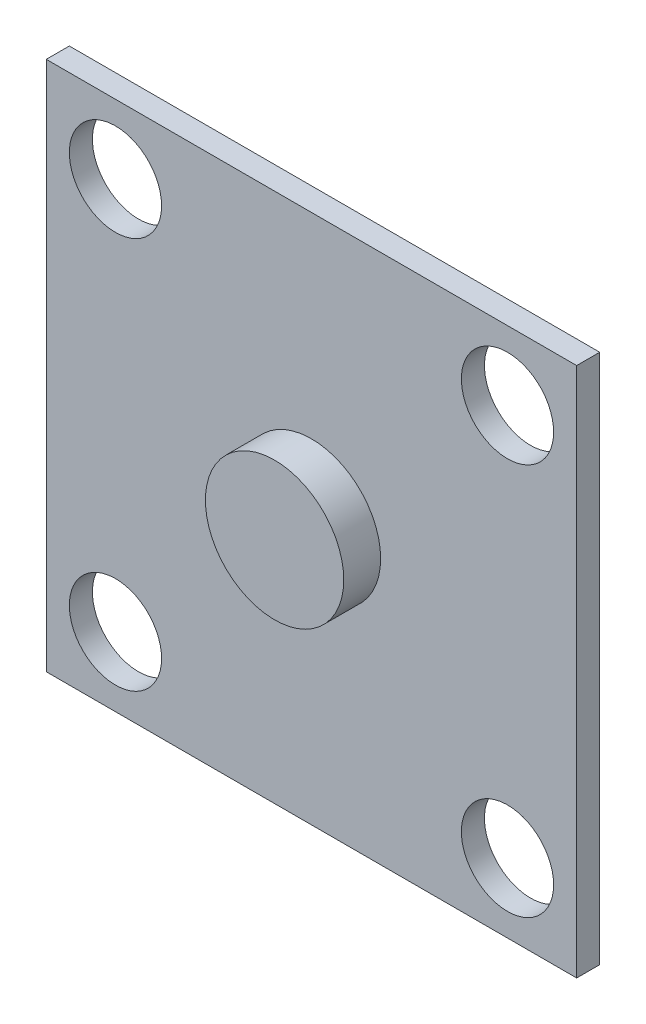
SolidWorks part; units mm, degrees
ref_plane "前视基准面" through (0, 0, 0) normal (0, 0, 1) x (1, 0, 0)
ref_plane "上视基准面" through (0, 0, 0) normal (0, 1, 0) x (1, 0, 0)
ref_plane "右视基准面" through (0, 0, 0) normal (1, 0, 0) x (0, 0, -1)
sketch "草图1" plane through (0, 0, 0) normal (0, 0, 1) x (1, 0, 0)
  line L1 (-11.776, 14.1224) -> (5.224, 14.1224) construction
  line L2 (-11.776, 14.1224) -> (-11.776, -2.8776) construction
  line L3 (-11.776, -2.8776) -> (5.224, -2.8776) construction
  line L4 (5.224, 14.1224) -> (5.224, -2.8776) construction
  line L5 (-11.776, 14.1224) -> (5.224, -2.8776) construction
  line L6 (-11.776, -2.8776) -> (5.224, 14.1224) construction
  line L7 (-14.776, 17.1224) -> (8.224, 17.1224)
  line L8 (-14.776, 17.1224) -> (-14.776, -5.8776)
  line L9 (-14.776, -5.8776) -> (8.224, -5.8776)
  line L10 (8.224, 17.1224) -> (8.224, -5.8776)
  line L11 (-14.776, 17.1224) -> (8.224, -5.8776) construction
  line L12 (-14.776, -5.8776) -> (8.224, 17.1224) construction
  circle A0 centre (-11.776, 14.1224) radius 2
  circle A1 centre (-11.776, -2.8776) radius 2
  circle A2 centre (5.224, -2.8776) radius 2
  circle A3 centre (5.224, 14.1224) radius 2
  point P0 (-3.276, 5.6224)
  point P9 (-3.276, 5.6224)
  dimension "D3" = 23
  dimension "D1" = 17
  dimension "D2" = 17
  dimension "D4" = 23
extrude "凸台-拉伸1" add sketch "草图1" along normal blind 1
sketch "草图2" plane through (0, 0, 1) normal (0, 0, 1) x (1, 0, 0)
  line L0 (-3.276, 17.1224) -> (-3.276, -5.8776) construction
  line L1 (8.224, 17.1224) -> (-14.776, 17.1224) construction
  line L2 (-14.776, -5.8776) -> (8.224, -5.8776) construction
  circle A0 centre (-3.276, 5.6224) radius 3
extrude "凸台-拉伸2" add sketch "草图2" along normal blind 1.6
